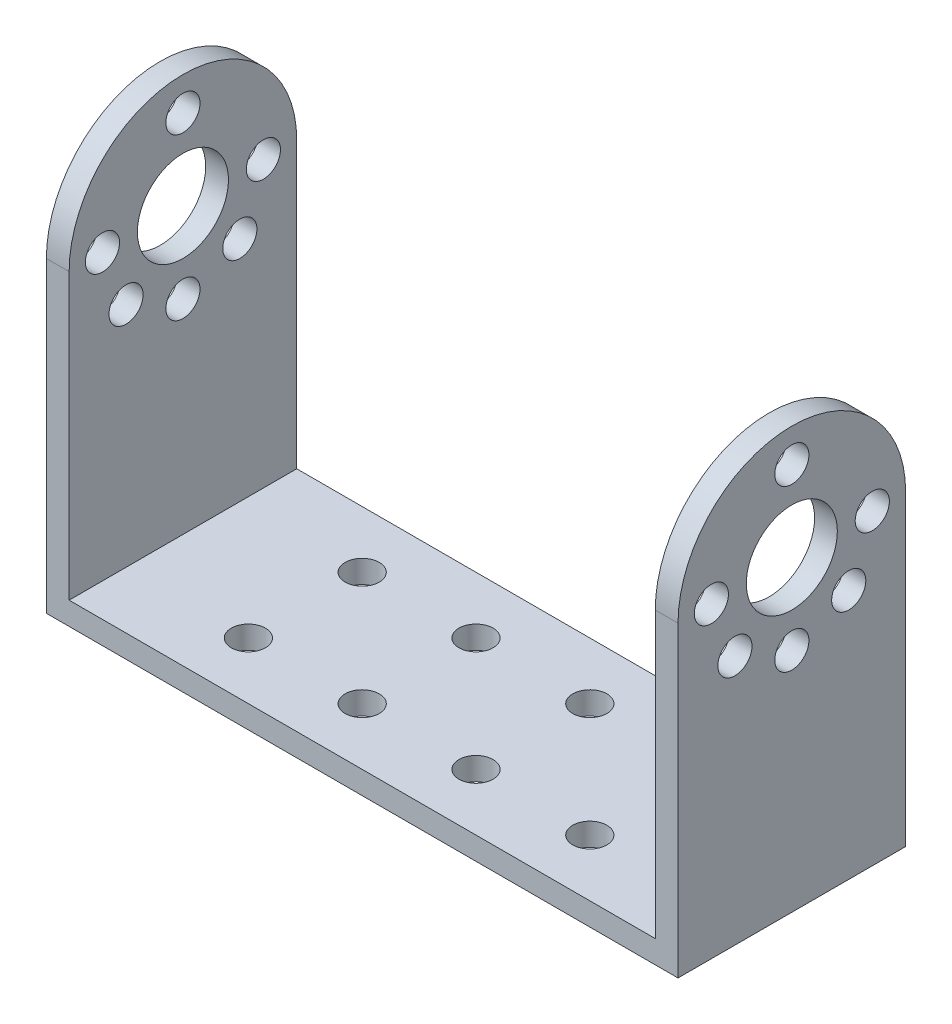
SolidWorks part; units mm, degrees
ref_plane "정면" through (0, 0, 0) normal (0, 0, 1) x (1, 0, 0)
ref_plane "윗면" through (0, 0, 0) normal (0, 1, 0) x (1, 0, 0)
ref_plane "우측면" through (0, 0, 0) normal (1, 0, 0) x (0, 0, -1)
sketch "스케치2" plane through (0, 0, 0) normal (0, 1, 0) x (1, 0, 0)
  line L0 (0, 10) -> (0, -10) construction
  line L1 (27.75, -10) -> (-27.75, -10)
  line L2 (27.75, -10) -> (27.75, 10)
  line L3 (27.75, 10) -> (-27.75, 10)
  line L4 (-27.75, -10) -> (-27.75, 10)
  line L5 (27.75, -10) -> (-27.75, 10) construction
  line L6 (27.75, 10) -> (-27.75, -10) construction
  circle A0 centre (-15, 5) radius 1.5
  circle A1 centre (-5, 5) radius 1.5
  circle A2 centre (-15, -5) radius 1.5
  circle A3 centre (-5, -5) radius 1.5
  circle A4 centre (15, -5) radius 1.5
  circle A5 centre (5, -5) radius 1.5
  circle A6 centre (5, 5) radius 1.5
  circle A7 centre (15, 5) radius 1.5
  point P0 (0, 0)
  point P6 (-15, 5)
  point P7 (-5, 5)
  point P8 (-15, -5)
  point P9 (-5, -5)
  dimension "D1" = 55.5
  dimension "D2" = 20
  dimension "D3" = 12.75
  dimension "D4" = 5
  dimension "D5" = 10
  dimension "D6" = 5
  dimension "D7" = 10
  dimension "D8" = 10
extrude "보스-돌출1" add sketch "스케치2" along normal blind 2
ref_plane "평면1" through (0, 2, 0) normal (0, 1, 0) x (1, 0, 0)
sketch "스케치3" plane through (0, 2, 0) normal (0, 1, 0) x (1, 0, 0)
  line L0 (-27.75, -10) -> (27.75, -10) construction
  line L1 (-27.75, 10) -> (-25.75, 10)
  line L2 (-27.75, 10) -> (-27.75, -10)
  line L3 (-27.75, -10) -> (-25.75, -10)
  line L4 (-25.75, 10) -> (-25.75, -10)
  line L6 (27.75, 10) -> (25.75, 10)
  line L7 (27.75, 10) -> (27.75, -10)
  line L8 (27.75, -10) -> (25.75, -10)
  line L9 (25.75, 10) -> (25.75, -10)
  dimension "D1" = 2
  dimension "D2" = 2
extrude "보스-돌출2" add sketch "스케치3" along normal blind 35
ref_plane "평면2" through (27.75, 0, 0) normal (1, 0, 0) x (0, 0, -1)
sketch "스케치4" plane through (27.75, 0, 0) normal (1, 0, 0) x (0, 0, -1)
  line L0 (-10, 37) -> (-10, 0) construction
  line L1 (-10, 0) -> (10, 0) construction
  line L2 (10, 37) -> (10, 0) construction
  line L3 (-10, 27) -> (-10, 37)
  line L4 (-10, 37) -> (10, 37)
  line L5 (10, 37) -> (10, 27)
  line L6 (-10, 27) -> (10, 27) construction
  line L7 (0, 37) -> (0, 0) construction
  arc A0 (10, 27) -> (-10, 27) centre (0, 27) ccw
  circle A1 centre (0, 27) radius 4
  circle A2 centre (0, 34.07) radius 1.5
  circle A3 centre (0, 19.93) radius 1.5
  circle A4 centre (-7.07, 27) radius 1.5
  circle A5 centre (7.07, 27) radius 1.5
  circle A6 centre (-4.9992, 22.0008) radius 1.5
  circle A7 centre (0, 19.93) radius 1.5
  circle A8 centre (4.9992, 22.0008) radius 1.5
  circle A9 centre (7.07, 27) radius 1.5
  point P0 (0, 27)
  point P15 (0, 34.07)
  point P20 (-7.07, 27)
  point P39 (0, 27)
  dimension "D3" = 7.07
  dimension "D4" = 7.07
  dimension "D5" = 5
  dimension "D1" = 10
  dimension "D2" = 27
extrude "컷-돌출1" cut sketch "스케치4" against normal blind 65 contours A0 L4 L3 | A0 L5 L4 | A5 | A1 | A2 | A8 | A3 | A6 | A4
